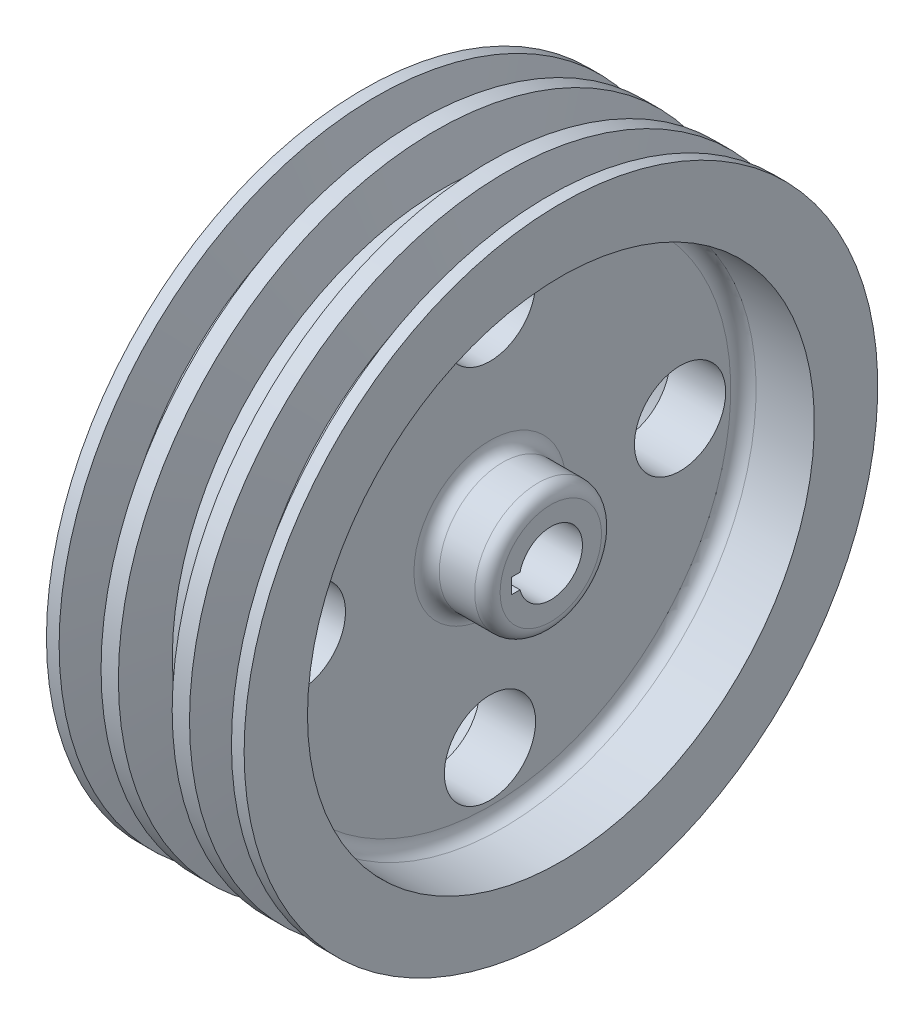
SolidWorks part; units mm, degrees
ref_plane "Front Plane" through (0, 0, 0) normal (0, 0, 1) x (1, 0, 0)
ref_plane "Top Plane" through (0, 0, 0) normal (0, 1, 0) x (1, 0, 0)
ref_plane "Right Plane" through (0, 0, 0) normal (1, 0, 0) x (0, 0, -1)
sketch "Sketch1" plane through (0, 0, 0) normal (0, 0, 1) x (1, 0, 0)
  line L0 (0, 0) -> (0, 125) construction
  line L1 (-10.6114, 125) -> (-17.4485, 125)
  line L3 (0, 12.5) -> (-35, 12.5)
  line L4 (0, 12.5) -> (35, 12.5)
  line L5 (-39, 125) -> (-39, 100)
  line L6 (-39, 100) -> (-16, 100)
  line L7 (-11, 95) -> (-11, 30)
  line L8 (-16, 25) -> (-30, 25)
  line L9 (-35, 20) -> (-35, 12.5)
  line L10 (11, 95) -> (11, 30)
  line L11 (16, 25) -> (30, 25)
  line L12 (39, 100) -> (16, 100)
  line L13 (39, 125) -> (39, 100)
  line L14 (35, 20) -> (35, 12.5)
  line L15 (-121.5853, 0) -> (165.0029, 0) construction
  line L16 (-7.3356, 107) -> (7.3356, 107)
  line L17 (-7.3356, 107) -> (-10.6114, 125)
  line L18 (-10.6114, 125) -> (-17.4485, 125)
  line L20 (-20.7243, 107) -> (-30.7243, 107)
  line L21 (-30.7243, 107) -> (-34, 125)
  line L22 (-34, 125) -> (-39, 125)
  line L23 (10.6114, 125) -> (17.4485, 125)
  line L25 (34, 125) -> (39, 125)
  line L26 (10.6114, 125) -> (17.4485, 125)
  line L27 (20.7243, 107) -> (30.7243, 107)
  line L28 (7.3356, 107) -> (10.6114, 125)
  line L29 (30.7243, 107) -> (34, 125)
  line L30 (-17.4485, 125) -> (-20.7243, 107)
  line L31 (-25.7243, 107) -> (-25.7243, 114.8779) construction
  line L32 (17.4485, 125) -> (20.7243, 107)
  arc A0 (16, 25) -> (11, 30) centre (16, 30) cw
  arc A1 (-11, 30) -> (-16, 25) centre (-16, 30) cw
  arc A2 (16, 100) -> (11, 95) centre (16, 95) ccw
  arc A3 (-11, 95) -> (-16, 100) centre (-16, 95) ccw
  arc A4 (35, 20) -> (30, 25) centre (30, 20) ccw
  arc A5 (-30, 25) -> (-35, 20) centre (-30, 20) ccw
  point P26 (0, 107)
  point P29 (25.7243, 107)
  point P34 (0, 107)
  point P37 (11, 25)
  point P40 (-11, 25)
  point P43 (11, 100)
  point P46 (-11, 100)
  point P49 (35, 25)
  point P52 (-35, 25)
  dimension "D14" = 5
  dimension "D2" = 125
  dimension "D3" = 12.5
  dimension "D4" = 70
  dimension "D5" = 25
  dimension "D6" = 78
  dimension "D7" = 22
  dimension "D8" = 5
  dimension "D9" = 18
  dimension "D10" = 5
  dimension "D11" = 10.6114
  dimension "D12" = 16.5515
  dimension "D13" = 25
revolve "Revolve2" add sketch "Sketch1" angle 360 about L15
sketch "Sketch2" plane through (-11, 0, 0) normal (-1, 0, 0) x (0, 0, 1)
  line L0 (0, 0) -> (0, 98.6003) construction
  line L1 (0, 0) -> (0, -95.1648) construction
  line L4 (15.5, -3) -> (15.5, 3)
  line L5 (15.5, 3) -> (12.1347, 3)
  line L6 (15.5, -3) -> (12.1347, -3)
  line L7 (15.5, 0) -> (95.6801, 0) construction
  arc A0 (12.1347, 3) -> (12.1347, -3) centre (0, 0) ccw
  circle A1 centre (0, 75) radius 18
  circle A2 centre (75, 0) radius 18
  circle A3 centre (0, -75) radius 18
  circle A4 centre (-75, 0) radius 18
  circle A5 centre (0, 0) radius 25 construction
  point P21 (0, 0)
  dimension "D1" = 75
  dimension "D3" = 36
  dimension "D4" = 12.1347
  dimension "D5" = 15.5
  dimension "D7" = 12.5
  dimension "D2" = 4
extrude "Cut-Extrude1" cut sketch "Sketch2" against normal through all both and the other way through all
